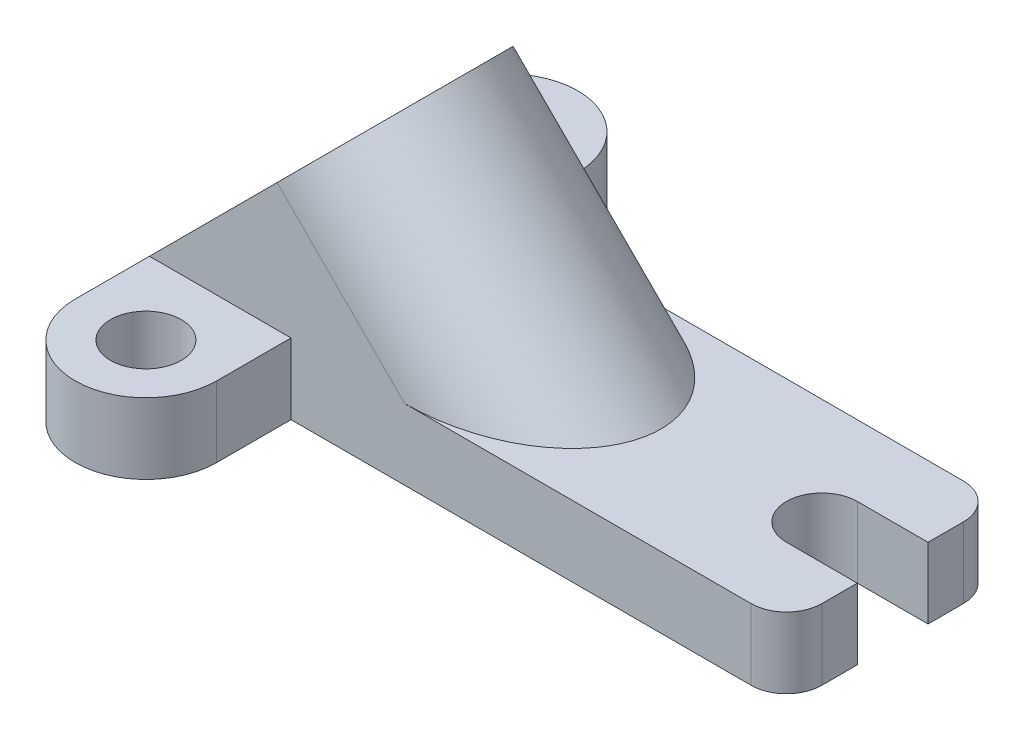
SolidWorks part; units mm, degrees
ref_plane "Front Plane" through (0, 0, 0) normal (0, 0, 1) x (1, 0, 0)
ref_plane "Top Plane" through (0, 0, 0) normal (0, 1, 0) x (1, 0, 0)
ref_plane "Right Plane" through (0, 0, 0) normal (1, 0, 0) x (0, 0, -1)
sketch "Sketch1" plane through (0, 0, 0) normal (0, 1, 0) x (1, 0, 0)
  line L0 (0, 51) -> (0, -51)
  line L1 (40, -51) -> (40, -30)
  line L2 (40, -30) -> (170, -30)
  line L3 (180, -20) -> (180, -10)
  line L4 (180, -10) -> (160, -10)
  line L5 (0, 0) -> (150, 0) construction
  line L6 (180, 10) -> (160, 10)
  line L7 (180, 20) -> (180, 10)
  line L8 (40, 30) -> (170, 30)
  line L9 (40, 51) -> (40, 30)
  arc A0 (0, -51) -> (40, -51) centre (20, -51) ccw
  arc A1 (170, -30) -> (180, -20) centre (170, -20) ccw
  arc A2 (160, -10) -> (160, 10) centre (160, 0) cw
  circle A3 centre (20, -51) radius 10
  circle A4 centre (20, 51) radius 10
  arc A5 (170, 30) -> (180, 20) centre (170, 20) cw
  arc A6 (0, 51) -> (40, 51) centre (20, 51) cw
  dimension "D2" = 20
  dimension "D4" = 30
  dimension "D5" = 10
  dimension "D8" = 10
  dimension "D9" = 20
  dimension "D1" = 51
  dimension "D3" = 180
  dimension "D6" = 10
  dimension "D7" = 20
extrude "Boss-Extrude1" add sketch "Sketch1" along normal blind 20
ref_plane "Plane1" through (-10, 10, 0) normal (-0.7071, 0.7071, 0) x (0, 0, 1)
sketch "Sketch2" plane through (-10, 10, 0) normal (-0.7071, 0.7071, 0) x (0, 0, 1)
  line L0 (30, 14.1421) -> (-30, 14.1421)
  line L1 (-51, 14.1421) -> (51, 14.1421) construction
  line L2 (-30, 14.1421) -> (-30, 65.1421)
  line L3 (-30, 134.3503) -> (-30, 42.4264) construction
  line L4 (30, 42.4264) -> (30, 134.3503) construction
  line L5 (30, 65.1421) -> (30, 14.1421)
  arc A0 (-30, 65.1421) -> (30, 65.1421) centre (0, 65.1421) cw
  point P11 (0, 0)
  dimension "D1" = 51
extrude "Boss-Extrude2" add sketch "Sketch2" against normal up to surface (51 mm away)
sketch "Sketch3" plane through (-10, 10, 0) normal (-0.7071, 0.7071, 0) x (0, 0, 1)
  circle A0 centre (0, 65.1421) radius 15
  arc A1 (30, 65.1421) -> (-30, 65.1421) centre (0, 65.1421) ccw construction
  dimension "D1" = 30
extrude "Cut-Extrude1" cut sketch "Sketch3" against normal up to surface (64.2843 mm away)
